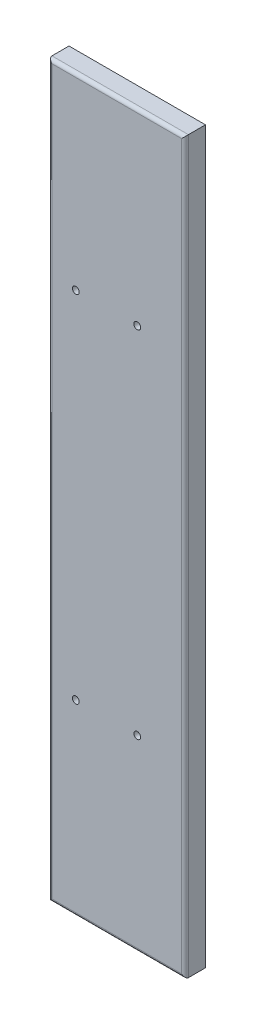
SolidWorks part; units mm, degrees
material "Pine"
ref_plane "Front Plane" through (0, 0, 0) normal (0, 0, 1) x (1, 0, 0)
ref_plane "Top Plane" through (0, 0, 0) normal (0, 1, 0) x (1, 0, 0)
ref_plane "Right Plane" through (0, 0, 0) normal (1, 0, 0) x (0, 0, -1)
sketch "Sketch1" plane through (0, 0, 0) normal (0, 0, 1) x (1, 0, 0)
  line L0 (-50.8, 25.4) -> (-53.975, 25.4)
  line L2 (-53.975, 174.625) -> (73.025, 174.625)
  line L3 (73.025, 174.625) -> (73.025, -504.825)
  line L4 (73.025, -504.825) -> (-53.975, -504.825)
  line L6 (-53.975, -504.825) -> (-53.975, 174.625)
extrude "Boss-Extrude1" add sketch "Sketch1" along normal blind 19.05 contours L3 L4 L6 L2
sketch "Sketch5" plane through (0, 0, 0) normal (0, 0, -1) x (-1, 0, 0)
  line L0 (53.975, -504.825) -> (53.975, -330.2) construction
  line L1 (53.975, -504.825) -> (53.975, 174.625) construction
  line L2 (53.975, -330.2) -> (28.575, -330.2) construction
  line L3 (28.575, -330.2) -> (-28.575, -330.2) construction
  line L4 (53.975, -330.2) -> (53.975, 0) construction
  line L5 (53.975, 0) -> (28.575, 0) construction
  line L6 (28.575, 0) -> (-28.575, 0) construction
  point P11 (0, 0)
hole_wizard "1/4 (0.25) Diameter Hole1" positions "Sketch3" profile "Sketch4" hole size "1/4" standard "ANSI Inch" end condition through all
sketch "Sketch3" plane through (0, 0, 19.05) normal (0, 0, 1) x (1, 0, 0)
  point P14 (-28.575, -330.2)
  point P17 (28.575, -330.2)
  point P23 (-28.575, 0)
  point P26 (28.575, 0)
sketch "Sketch4" plane through (-28.575, -330.2, 19.05) normal (1, 0, 0) x (0, -1, 0)
  line L0 (0, 0) -> (0, 19.05)
  line L1 (0, 19.05) -> (3.937, 19.05)
  line L2 (3.175, 18.1734) -> (3.175, 0)
  line L5 (3.175, 0) -> (0, 0)
  line L7 (3.937, 19.05) -> (3.175, 18.1734)
  line L8 (-3.937, 19.05) -> (-3.175, 18.1734) construction
  line L11 (0, -6.35) -> (0, 107.95) construction
  dimension "Thru Hole Dia." = 6.35
  dimension "Thru Hole Depth" = 19.05
  dimension "Far C'Sink Dia." = 7.874
  dimension "Far C'Sink Angle" = 82
fillet "Fillet1" radius 3.175 4 edges at (9.525, 174.625, 19.05) (9.525, -504.825, 19.05) (73.025, -165.1, 19.05) (-53.975, -165.1, 19.05)
